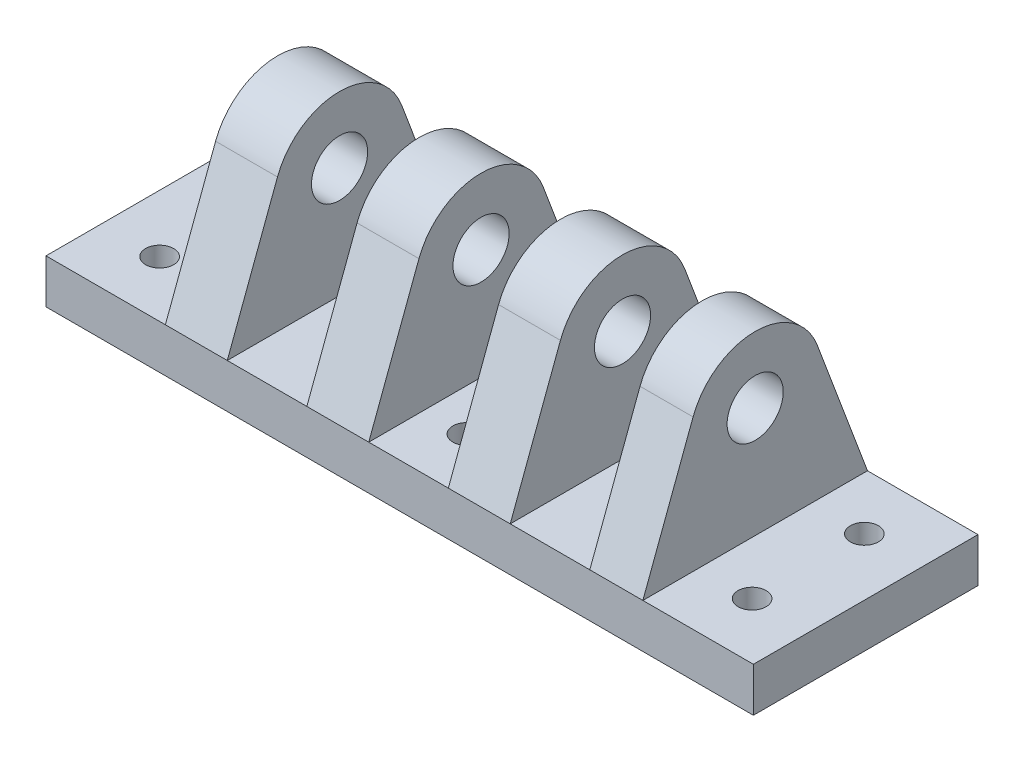
SolidWorks part; units mm, degrees
ref_plane "Front Plane" through (0, 0, 0) normal (0, 0, 1) x (1, 0, 0)
ref_plane "Top Plane" through (0, 0, 0) normal (0, 1, 0) x (1, 0, 0)
ref_plane "Right Plane" through (0, 0, 0) normal (1, 0, 0) x (0, 0, -1)
sketch "Sketch1" plane through (0, 0, 0) normal (0, 1, 0) x (1, 0, 0)
  line L1 (0, 0) -> (160, 0)
  line L2 (0, 0) -> (0, 50.8)
  line L3 (0, 50.8) -> (160, 50.8)
  line L4 (160, 0) -> (160, 50.8)
  dimension "D1" = 160
  dimension "D2" = 50.8
extrude "Boss-Extrude1" add sketch "Sketch1" along normal blind 10
sketch "Sketch2" plane through (0, 0, 0) normal (-1, 0, 0) x (0, 0, 1)
  line L0 (-50.8, 10) -> (-39.4442, 40.2689)
  line L1 (0, 10) -> (-11.3558, 40.2689)
  line L2 (-50.8, 10) -> (0, 10)
  arc A0 (-39.4442, 40.2689) -> (-11.3558, 40.2689) centre (-25.4, 35) cw
  circle A1 centre (-25.4, 35) radius 6.35
  point P8 (-25.4, 50)
  dimension "D2" = 12.7
  dimension "D1" = 25
  dimension "D3" = 40
extrude "Boss-Extrude2" add sketch "Sketch2" against normal through all
sketch "Sketch3" plane through (0, 0, -50.8) normal (0, 0, -1) x (-1, 0, 0)
  line L0 (-27, 10) -> (-27, 50)
  line L1 (-160, 10) -> (0, 10) construction
  line L2 (0, 50) -> (-160, 50) construction
  line L3 (-27, 50) -> (0, 50)
  line L4 (0, 50) -> (0, 10)
  line L5 (0, 10) -> (-27, 10)
  line L16 (0, 40.2689) -> (0, 10) construction
  line L24 (-41, 10) -> (-59, 10)
  line L25 (-41, 10) -> (-41, 50)
  line L26 (-41, 50) -> (-59, 50)
  line L27 (-59, 10) -> (-59, 50)
  line L28 (0, 50) -> (-160, 50) construction
  line L30 (-73, 10) -> (-91, 10)
  line L31 (-73, 10) -> (-73, 50)
  line L32 (-73, 50) -> (-91, 50)
  line L33 (-91, 10) -> (-91, 50)
  line L34 (-105, 10) -> (-123, 10)
  line L35 (-105, 10) -> (-105, 50)
  line L36 (-105, 50) -> (-123, 50)
  line L37 (-123, 10) -> (-123, 50)
  line L38 (-160, 10) -> (-135, 10)
  line L39 (-160, 10) -> (-160, 50)
  line L40 (-160, 50) -> (-135, 50)
  line L41 (-135, 10) -> (-135, 50)
  point P20 (-73, 30)
  dimension "D1" = 27
  dimension "D2" = 14
  dimension "D3" = 18
  dimension "D4" = 0
  dimension "D5" = 14
  dimension "D6" = 18
  dimension "D7" = 14
  dimension "D8" = 18
  dimension "D9" = 25
extrude "Cut-Extrude2" cut sketch "Sketch3" against normal through all
hole_wizard "#4 (0.25) Diameter Hole1" positions "Sketch5" profile "Sketch7" hole size "#4" standard "ANSI Inch" end condition through all
sketch "Sketch5" plane through (0, 10, 0) normal (0, 1, 0) x (1, 0, 0)
  line L0 (13, 38.1) -> (13, 12.7)
  line L3 (13, 12.7) -> (160, 12.7)
  line L4 (160, 10.4) -> (160, 40.4) construction
  line L6 (13, 38.1) -> (160, 38.1)
  line L8 (27, 0) -> (0, 0) construction
  line L9 (0, 40.4) -> (0, 10.4) construction
  line L10 (147, 12.7) -> (147, 38.1)
  line L12 (82.5, 12.7) -> (82.5, 38.1)
  point P0 (82.5, 38.1)
  point P3 (82.5, 12.7)
  point P9 (147, 12.7)
  point P11 (147, 38.1)
  point P12 (13, 38.1)
  point P14 (13, 12.7)
  dimension "D1" = 25.4
  dimension "D2" = 12.7
  dimension "D3" = 69.5
  dimension "D4" = 13
  dimension "D5" = 13
sketch "Sketch7" plane through (82.5, 10, -38.1) normal (1, 0, 0) x (0, 0, 1)
  line L0 (0, 0) -> (0, 10)
  line L1 (0, 10) -> (3.175, 10)
  line L2 (3.175, 10) -> (3.175, 0)
  line L5 (3.175, 0) -> (0, 0)
  line L11 (0, -6.35) -> (0, 107.95) construction
  dimension "Thru Hole Dia." = 6.35
  dimension "Thru Hole Depth" = 10
